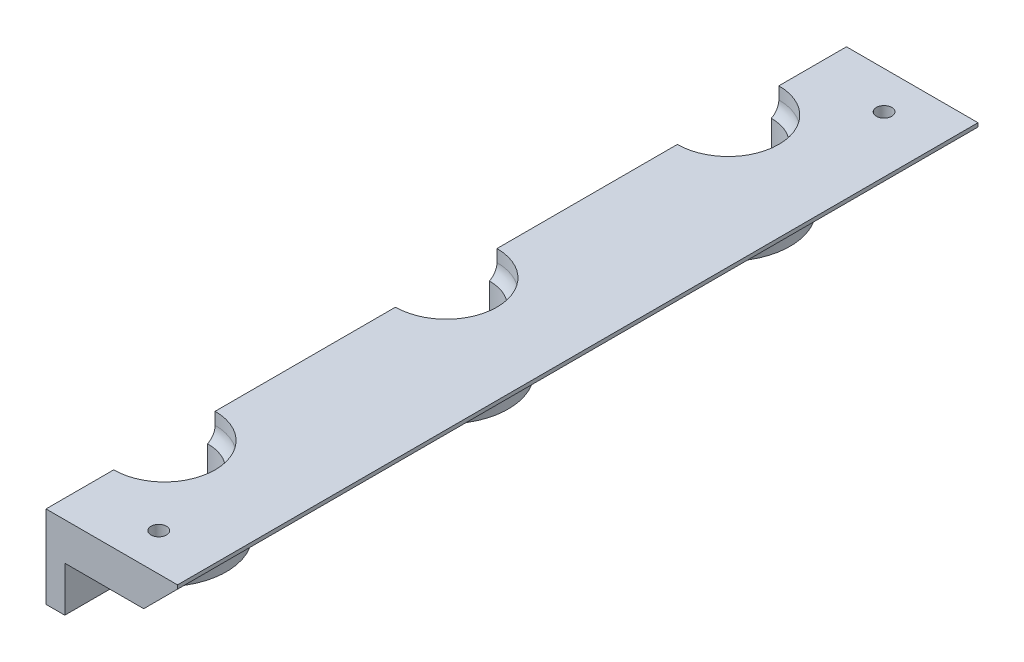
SolidWorks part; units mm, degrees
ref_plane "Płaszczyzna przednia" through (0, 0, 0) normal (0, 0, 1) x (1, 0, 0)
ref_plane "Płaszczyzna górna" through (0, 0, 0) normal (0, 1, 0) x (1, 0, 0)
ref_plane "Płaszczyzna prawa" through (0, 0, 0) normal (1, 0, 0) x (0, 0, -1)
sketch "Sketch1" plane through (0, 0, 0) normal (0, 1, 0) x (1, 0, 0)
  line L0 (0, 65.8555) -> (0, -65.8555) construction
  line L1 (0, -11.5) -> (0, -31.5)
  line L2 (0, -31.5) -> (35, -31.5)
  line L3 (104.3478, 75) -> (-104.3478, 75) construction
  line L4 (35, -31.5) -> (35, 181.5)
  line L5 (0, 161.5) -> (0, 181.5)
  line L6 (0, 181.5) -> (35, 181.5)
  line L7 (0, 11.5) -> (0, 63.5)
  line L8 (0, 86.5) -> (0, 138.5)
  circle A0 centre (0, 0) radius 11 construction
  circle A3 centre (0, 75) radius 11 construction
  circle A5 centre (0, 150) radius 11 construction
  arc A6 (0, -11.5) -> (0, 11.5) centre (0, 0) ccw
  arc A7 (0, 63.5) -> (0, 86.5) centre (0, 75) ccw
  arc A8 (0, 138.5) -> (0, 161.5) centre (0, 150) ccw
  point P7 (0, 0)
  point P20 (0, 75)
  point P23 (35, 75)
  dimension "D1" = 22
  dimension "D2" = 11.5
  dimension "D3" = 3
  dimension "D6" = 3
  dimension "D4" = 20
  dimension "D5" = 35
extrude "Boss-Extrude1" add sketch "Sketch1" against normal blind 10
sketch "Sketch3" plane through (0, -10, 0) normal (0, -1, 0) x (1, 0, 0)
  line L23 (0, -181.5) -> (0, -161.5)
  line L24 (0, -138.5) -> (0, -86.5)
  line L25 (0, -63.5) -> (0, -11.5)
  line L26 (0, 11.5) -> (0, 31.5)
  line L27 (5, -181.5) -> (5, -165.7242)
  line L28 (5, -134.2758) -> (5, -90.7242)
  line L29 (5, -59.2758) -> (5, -15.7242)
  line L30 (5, 15.7242) -> (5, 31.5)
  line L31 (5, -181.5) -> (5, -165.7242)
  line L32 (5, -134.2758) -> (5, -90.7242)
  line L33 (5, -59.2758) -> (5, -15.7242)
  line L34 (5, 15.7242) -> (5, 31.5)
  line L35 (0, 31.5) -> (5, 31.5)
  line L36 (0, -181.5) -> (5, -181.5)
  arc A15 (0, -161.5) -> (0, -138.5) centre (0, -150) ccw
  arc A16 (0, -86.5) -> (0, -63.5) centre (0, -75) ccw
  arc A17 (0, -11.5) -> (0, 11.5) centre (0, 0) ccw
  arc A18 (5, -165.7242) -> (5, -134.2758) centre (0, -150) ccw
  arc A19 (5, -90.7242) -> (5, -59.2758) centre (0, -75) ccw
  arc A20 (5, -15.7242) -> (5, 15.7242) centre (0, 0) ccw
  arc A21 (5, -165.7242) -> (5, -134.2758) centre (0, -150) ccw
  arc A22 (5, -90.7242) -> (5, -59.2758) centre (0, -75) ccw
  arc A23 (5, -15.7242) -> (5, 15.7242) centre (0, 0) ccw
  dimension "D1" = 5
extrude "Boss-Extrude2" add sketch "Sketch3" along normal blind 12
sketch "Sketch7" plane through (0, 0, 0) normal (-1, 0, 0) x (0, 0, 1)
  line L0 (-161.5, 0) -> (-174.5, 0) construction
  line L1 (-181.5, 0) -> (-161.5, 0) construction
  line L2 (-174.5, 0) -> (-174.5, -22) construction
  line L3 (-161.5, -22) -> (-181.5, -22) construction
  line L4 (-174.5, -11) -> (-161.5, -11) construction
  line L5 (-161.5, -22) -> (-161.5, 0) construction
  line L7 (-150, 0) -> (-150, -22) construction
  line L8 (-138.5, 0) -> (-161.5, 0) construction
  line L9 (-161.5, -22) -> (-138.5, -22) construction
  circle A0 centre (-170.5, -4) radius 1.95
  circle A1 centre (-170.5, -18) radius 1.95
  circle A2 centre (-129.5, -4) radius 1.95
  circle A3 centre (-129.5, -18) radius 1.95
  circle A4 centre (-95.5, -4) radius 1.95
  circle A5 centre (-54.5, -4) radius 1.95
  circle A6 centre (-54.5, -18) radius 1.95
  circle A7 centre (-95.5, -18) radius 1.95
  circle A8 centre (-20.5, -4) radius 1.95
  circle A9 centre (20.5, -4) radius 1.95
  circle A10 centre (20.5, -18) radius 1.95
  circle A11 centre (-20.5, -18) radius 1.95
  dimension "D2" = 3.9
  dimension "D3" = 4
  dimension "D4" = 3
  dimension "D1" = 13
extrude "Cut-Extrude3" cut sketch "Sketch7" against normal blind 4
sketch "Sketch8" plane through (0, 0, 0) normal (-1, 0, 0) x (0, 0, 1)
  line L0 (-86.5, -22) -> (-138.5, -22) construction
  line L1 (-138.5, 0) -> (-112.5, -18.5) construction
  line L2 (-112.5, -18.5) -> (-86.5, 0) construction
  circle A0 centre (-112.5, -18.5) radius 1.95
  point P6 (0, 0)
  point P8 (0, 0)
  point P10 (0, 0)
  dimension "D1" = 3.9
  dimension "D2" = 3.5
extrude "Cut-Extrude4" cut sketch "Sketch8" against normal blind 4 contours A0
sketch "Sketch9" plane through (4, 0, 0) normal (-1, 0, 0) x (0, 0, 1)
  circle A0 centre (-112.5, -18.5) radius 1.5
  circle A1 centre (-112.5, -18.5) radius 1.95 construction
  dimension "D1" = 3
extrude "Cut-Extrude5" cut sketch "Sketch9" against normal blind 4
pattern_linear "LPattern1" count 2 spacing 75 along (0, 0, 1) of "Cut-Extrude4", "Cut-Extrude5"
chamfer "Chamfer1" distance 9 angle 45 1 edges at (35, -10, -75)
sketch "Sketch10" plane through (0, 0, 0) normal (-1, 0, 0) x (0, 0, 1)
  line L0 (-161.5, 0) -> (-161.5, -6.48)
  line L1 (-163.5, 0) -> (-161.5, 0)
  line L2 (-163.5, 0) -> (-163.5, -3.24)
  line L3 (-150, 19.0098) -> (-150, -30.936) construction
  line L4 (-161.5, -22) -> (-150, -30.936) construction
  line L5 (-150, -30.936) -> (-138.5, -22) construction
  arc A0 (-161.5, -6.48) -> (-163.5, -3.24) centre (-159.8756, -3.24) cw
  point P13 (0, 0)
  dimension "D1" = 6.48
  dimension "D2" = 2
  dimension "D4" = 49.9458
revolve "Cut-Revolve1" cut sketch "Sketch10" angle 360 about L3
pattern_linear "LPattern2" count 3 spacing 75 along (0, 0, 1) of "Cut-Revolve1"
sketch "Sketch12" plane through (0, 0, 0) normal (0, 1, 0) x (1, 0, 0)
  line L0 (0, -31.5) -> (20, -31.5) construction
  line L1 (20, -31.5) -> (20, -21.5) construction
  line L2 (0, -31.5) -> (35, -31.5) construction
  circle A0 centre (20, -21.5) radius 2.05
  point P4 (0, 0)
  point P9 (0, 0)
  dimension "D3" = 4.1
  dimension "D1" = 20
  dimension "D2" = 10
extrude "Cut-Extrude6" cut sketch "Sketch12" against normal blind 4
sketch "Sketch13" plane through (0, -4, 0) normal (0, 1, 0) x (1, 0, 0)
  circle A0 centre (20, -21.5) radius 1.6
  circle A2 centre (20, -21.5) radius 2.05 construction
  dimension "D1" = 3.2
extrude "Cut-Extrude8" cut sketch "Sketch13" against normal blind 5 contours A0
ref_plane "Plane1" through (0, 0, -75) normal (0, 0, 1) x (1, 0, 0)
mirror "Mirror2" about plane through (0, 0, -75) normal (0, 0, 1) of "Cut-Extrude8", "Cut-Extrude6"
